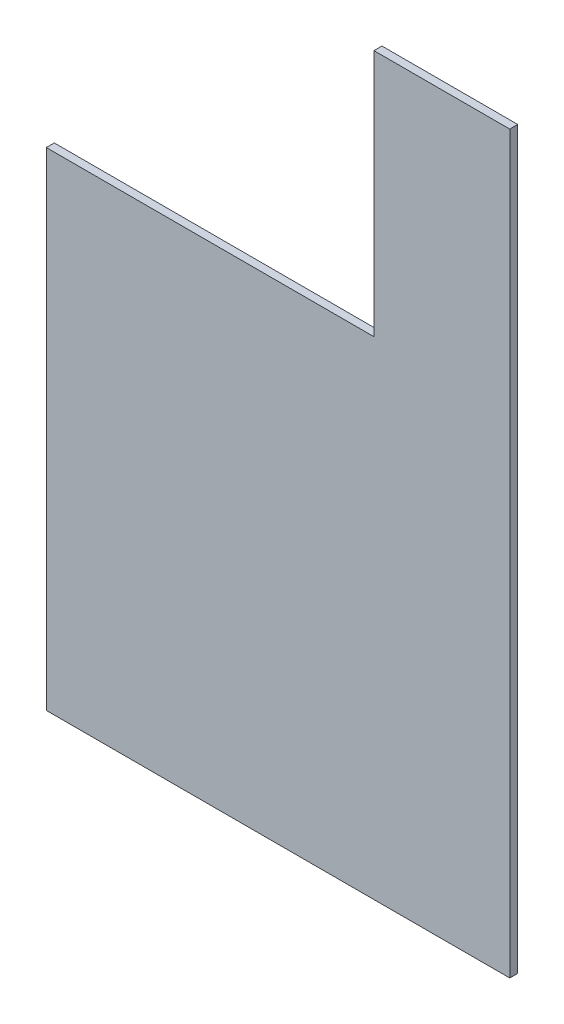
SolidWorks part; units mm, degrees
ref_plane "Plan de face" through (0, 0, 0) normal (0, 0, 1) x (1, 0, 0)
ref_plane "Plan de dessus" through (0, 0, 0) normal (0, 1, 0) x (1, 0, 0)
ref_plane "Plan de droite" through (0, 0, 0) normal (1, 0, 0) x (0, 0, -1)
sketch "Esquisse1" plane through (0, 0, 0) normal (0, 0, 1) x (1, 0, 0)
  line L0 (0, 122) -> (82, 122)
  line L1 (0, 0) -> (116, 0)
  line L2 (0, 0) -> (0, 122)
  line L3 (82, 184) -> (116, 184)
  line L4 (116, 0) -> (116, 184)
  line L5 (82, 122) -> (82, 184)
  dimension "D1" = 184
  dimension "D2" = 116
  dimension "D3" = 82
  dimension "D4" = 62
extrude "Boss.-Extru.1" add sketch "Esquisse1" along normal blind 2
